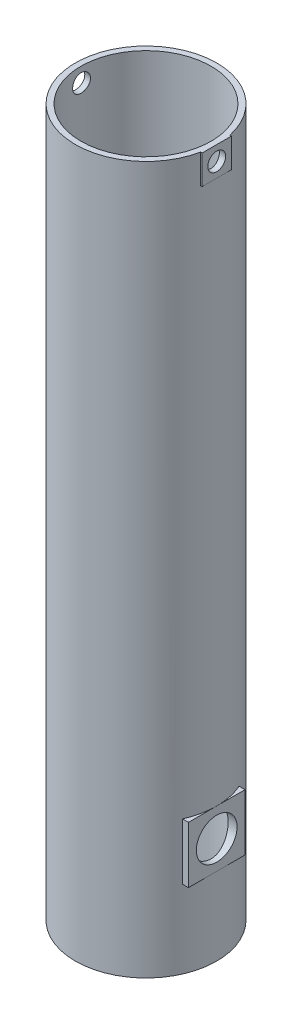
SolidWorks part; units mm, degrees
ref_plane "Front Plane" through (0, 0, 0) normal (0, 0, 1) x (1, 0, 0)
ref_plane "Top Plane" through (0, 0, 0) normal (0, 1, 0) x (1, 0, 0)
ref_plane "Right Plane" through (0, 0, 0) normal (1, 0, 0) x (0, 0, -1)
sketch "Sketch1" plane through (0, 0, 0) normal (0, 1, 0) x (1, 0, 0)
  circle A0 centre (0, 0) radius 6.35
  circle A1 centre (0, 0) radius 5.842
  dimension "D1" = 12.7
  dimension "D2" = 11.684
extrude "Boss-Extrude1" add sketch "Sketch1" along normal blind 63.5
ref_plane "Plane1" through (6.35, 0, 0) normal (1, 0, 0) x (0, 0, -1)
sketch "Sketch2" plane through (6.35, 0, 0) normal (1, 0, 0) x (0, 0, -1)
  line L0 (6.35, 63.5) -> (-6.35, 63.5) construction
  line L1 (6.35, 63.5) -> (-6.35, 63.5) construction
  line L2 (0, 63.5) -> (0, 62.1919) construction
  line L3 (-6.35, 62.992) -> (6.35, 62.992) construction
  line L4 (-6.35, 63.5) -> (-6.35, 0) construction
  line L5 (6.35, 0) -> (6.35, 63.5) construction
  circle A0 centre (0, 62.1919) radius 0.8001
  dimension "D1" = 1.6002
  dimension "D2" = 0.508
extrude "Cut-Extrude1" cut sketch "Sketch2" against normal through all
sketch "Sketch3" plane through (6.35, 0, 0) normal (1, 0, 0) x (0, 0, -1)
  line L0 (6.35, 63.5) -> (-6.35, 63.5) construction
  line L1 (1.3081, 60.8838) -> (-1.3081, 60.8838)
  line L2 (1.3081, 60.8838) -> (1.3081, 63.5)
  line L3 (1.3081, 63.5) -> (-1.3081, 63.5)
  line L4 (-1.3081, 60.8838) -> (-1.3081, 63.5)
  line L5 (1.3081, 60.8838) -> (-1.3081, 63.5) construction
  line L6 (1.3081, 63.5) -> (-1.3081, 60.8838) construction
  circle A0 centre (0, 62.1919) radius 0.8001 construction
  circle A1 centre (0, 62.1919) radius 0.8001
extrude "Boss-Extrude2" add sketch "Sketch3" against normal up to surface up to face at (-6.3475, 62.9722, 0.1769)
sketch "Sketch4" plane through (6.35, 0, 0) normal (1, 0, 0) x (0, 0, -1)
  line L0 (0, 0) -> (0, 9.525) construction
  circle A0 centre (0, 9.525) radius 1.8288
  dimension "D1" = 3.6576
  dimension "D2" = 9.525
extrude "Cut-Extrude2" cut sketch "Sketch4" against normal through all
sketch "Sketch5" plane through (6.35, 0, 0) normal (1, 0, 0) x (0, 0, -1)
  line L1 (-2.54, 6.985) -> (2.54, 6.985)
  line L2 (-2.54, 6.985) -> (-2.54, 12.065)
  line L3 (-2.54, 12.065) -> (2.54, 12.065)
  line L4 (2.54, 6.985) -> (2.54, 12.065)
  line L5 (-2.54, 6.985) -> (2.54, 12.065) construction
  line L6 (-2.54, 12.065) -> (2.54, 6.985) construction
  circle A0 centre (0, 9.525) radius 1.8288 construction
  circle A1 centre (0, 9.525) radius 1.8288
  dimension "D1" = 5.08
extrude "Boss-Extrude3" add sketch "Sketch5" against normal up to surface up to face at (-6.341, 11.3223, 0.3378)
